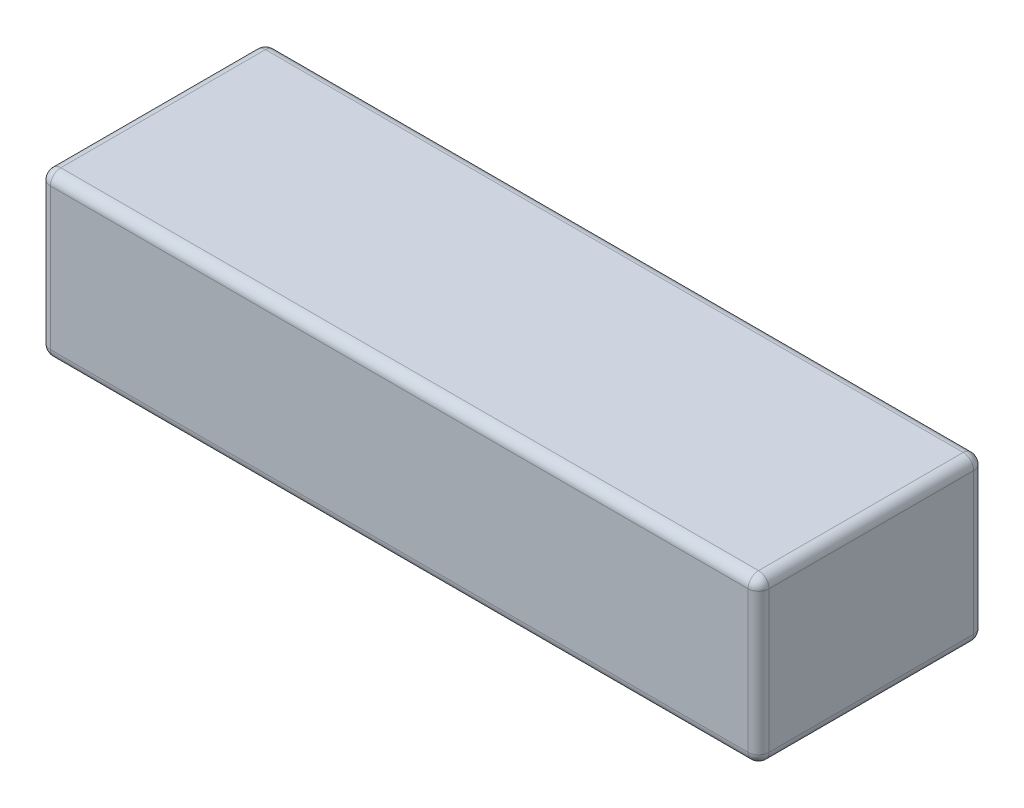
SolidWorks part; units mm, degrees
material "Custom Plastic"
ref_plane "Front Plane" through (0, 0, 0) normal (0, 0, 1) x (1, 0, 0)
ref_plane "Top Plane" through (0, 0, 0) normal (0, 1, 0) x (1, 0, 0)
ref_plane "Right Plane" through (0, 0, 0) normal (1, 0, 0) x (0, 0, -1)
sketch "Sketch1" plane through (0, 0, 0) normal (0, 1, 0) x (1, 0, 0)
  line L1 (0, 0) -> (137, 0)
  line L2 (0, 0) -> (0, 43)
  line L3 (0, 43) -> (137, 43)
  line L4 (137, 0) -> (137, 43)
  dimension "D1" = 137
  dimension "D2" = 43
extrude "Boss-Extrude1" add sketch "Sketch1" along normal blind 31
sketch "Sketch3" plane through (0, 0, 0) normal (0, 0, 1) x (1, 0, 0)
  text T0 "Battery" font "Century Gothic" height 15
sketch "Sketch4" plane through (0, 0, -43) normal (0, 0, -1) x (-1, 0, 0)
  text T0 "Battery" font "Century Gothic" height 10
fillet "Fillet1" radius 2 12 edges at (137, 15.5, 0) (137, 15.5, -43) (0, 15.5, -43) (0, 15.5, 0) (68.5, 0, 0) (137, 0, -21.5) (68.5, 0, -43) (0, 0, -21.5) (68.5, 31, -43) (137, 31, -21.5) (68.5, 31, 0) (0, 31, -21.5)
ref_plane "Plane1" through (0, 0, -21.5) normal (0, 0, 1) x (1, 0, 0)
ref_plane "Plane2" through (68.5, 0, 0) normal (-1, 0, 0) x (0, 0, 1)
